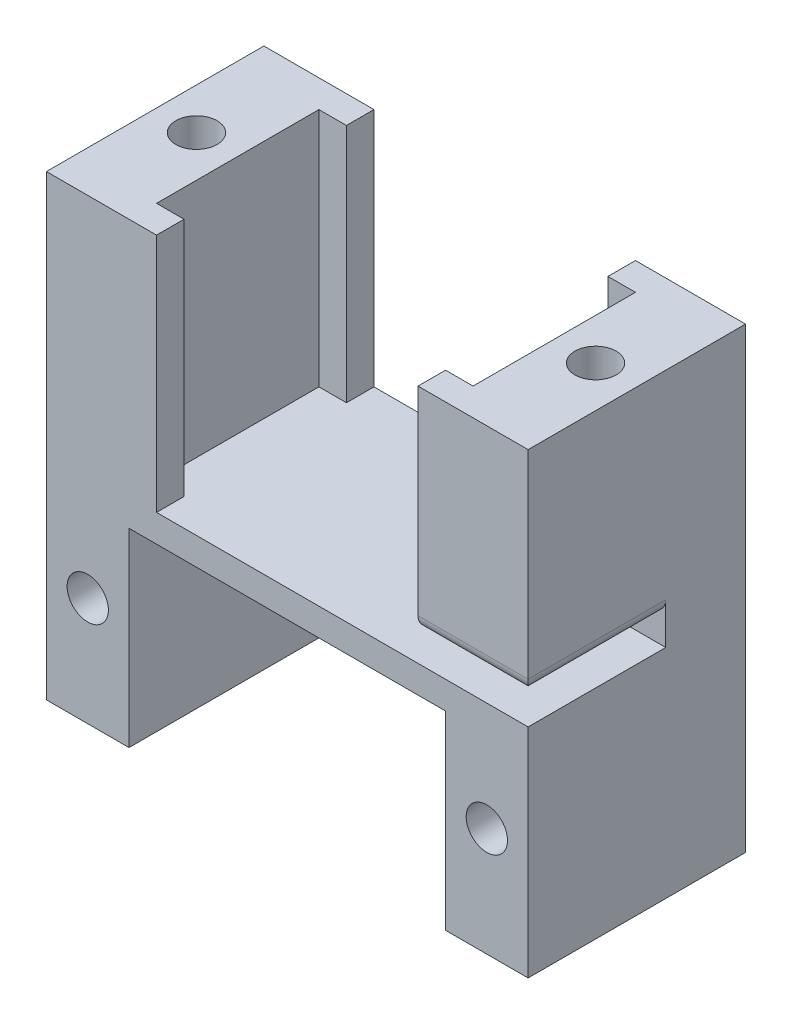
SolidWorks part; units mm, degrees
ref_plane "Front Plane" through (0, 0, 0) normal (0, 0, 1) x (1, 0, 0)
ref_plane "Top Plane" through (0, 0, 0) normal (0, 1, 0) x (1, 0, 0)
ref_plane "Right Plane" through (0, 0, 0) normal (1, 0, 0) x (0, 0, -1)
sketch "Sketch1" plane through (0, 0, 0) normal (0, 1, 0) x (1, 0, 0)
  line L0 (-3, -5.9) -> (-5, -5.9)
  line L1 (-3, 5.9) -> (3, 5.9) construction
  line L2 (-3, 5.9) -> (-3, -5.9)
  line L3 (-3, -5.9) -> (3, -5.9) construction
  line L4 (3, 5.9) -> (3, -5.9)
  line L5 (-3, 5.9) -> (3, -5.9) construction
  line L6 (-3, -5.9) -> (3, 5.9) construction
  line L7 (0, 0) -> (-3, 0) construction
  line L8 (-5, -5.9) -> (-5, -7.9)
  line L9 (-5, -7.9) -> (3, -7.9)
  line L10 (3, -7.9) -> (3, -5.9)
  line L11 (-3, 5.9) -> (-5, 5.9)
  line L12 (-5, 5.9) -> (-5, 7.9)
  line L13 (3, 7.9) -> (3, 5.9)
  line L14 (-5, 7.9) -> (3, 7.9)
  circle A0 centre (0, 0) radius 1.5
  point P0 (0, 0)
extrude "Boss-Extrude1" add sketch "Sketch1" against normal blind 19.45 contours L14 L12 L11 L2 L0 L8 L9 L10 L4 L13 A0
sketch "Sketch2" plane through (0, -19.45, 0) normal (0, -1, 0) x (1, 0, 0)
  circle A0 centre (0, 0) radius 1.5 construction
  circle A1 centre (0, 0) radius 1.5
extrude "Boss-Extrude2" add sketch "Sketch2" against normal blind 5
sketch "Sketch3" plane through (0, 0, 0) normal (0, 1, 0) x (1, 0, 0)
  line L0 (-3, -5.9) -> (-26, -5.9) construction
  line L1 (-14.5, -5.9) -> (-14.5, 3.6808) construction
sketch3d "3DSketch1"
  line L0 (-14.5, 0, 5.9) -> (-14.5, 0, -3.6808) construction
ref_plane "Plane1" through (-14.5, 0, 0) normal (-1, 0, 0) x (0, 0, 1)
mirror "Mirror2" about plane through (-14.5, 0, 0) normal (-1, 0, 0) of bodies 102
sketch "Sketch5" plane through (0, -19.45, 0) normal (0, -1, 0) x (1, 0, 0)
  line L0 (-32, 7.9) -> (3, 7.9)
  line L1 (3, 7.9) -> (3, -7.9)
  line L2 (3, -7.9) -> (-32, -7.9)
  line L3 (-32, -7.9) -> (-32, 7.9)
extrude "Boss-Extrude3" add sketch "Sketch5" against normal blind 2
sketch "Sketch6" plane through (0, 0, 7.9) normal (0, 0, 1) x (1, 0, 0)
  line L0 (-3, -31.25) -> (-5, -31.25)
  line L1 (-3, -19.45) -> (3, -19.45) construction
  line L2 (-3, -19.45) -> (-3, -31.25)
  line L3 (-3, -31.25) -> (3, -31.25) construction
  line L4 (3, -19.45) -> (3, -31.25)
  line L5 (-3, -19.45) -> (3, -31.25) construction
  line L6 (-3, -31.25) -> (3, -19.45) construction
  line L7 (0, -25.35) -> (-3, -25.35) construction
  line L8 (-5, -31.25) -> (-5, -33.25)
  line L9 (-5, -33.25) -> (3, -33.25)
  line L10 (3, -33.25) -> (3, -31.25)
  line L11 (-3, -19.45) -> (-5, -19.45)
  line L12 (-5, -19.45) -> (-5, -17.45)
  line L13 (3, -17.45) -> (3, -19.45)
  line L14 (-5, -17.45) -> (3, -17.45)
  line L15 (-32, -19.45) -> (3, -19.45) construction
  line L16 (-32, -19.45) -> (3, -19.45)
  line L17 (-14.5, -19.45) -> (-14.5, -10.6217) construction
  line L18 (-29, -25.35) -> (-26, -25.35) construction
  line L19 (-26, -31.25) -> (-32, -19.45) construction
  line L20 (-26, -19.45) -> (-32, -31.25) construction
  line L21 (-26, -31.25) -> (-32, -31.25) construction
  line L22 (-26, -19.45) -> (-32, -19.45) construction
  line L23 (-24, -17.45) -> (-32, -17.45)
  line L24 (-32, -17.45) -> (-32, -19.45)
  line L25 (-24, -19.45) -> (-24, -17.45)
  line L26 (-26, -19.45) -> (-24, -19.45)
  line L27 (-32, -33.25) -> (-32, -31.25)
  line L28 (-24, -33.25) -> (-32, -33.25)
  line L29 (-24, -31.25) -> (-24, -33.25)
  line L30 (-32, -19.45) -> (-32, -31.25)
  line L31 (-26, -19.45) -> (-26, -31.25)
  line L32 (-26, -31.25) -> (-24, -31.25)
  circle A0 centre (0, -25.35) radius 1.5
  circle A1 centre (-29, -25.35) radius 1.5
  point P0 (0, -25.35)
  point P31 (-29, -25.35)
  line M27 (-32, -19.45) -> (3, -19.45)
extrude "Boss-Extrude4" add sketch "Sketch6" against normal up to surface (15.8 mm away) contours L32 L31 L30 L27 L28 L29 A1 M27 | L9 L10 L4 L2 L0 L8 A0 M27 up to face at (-14.5, -9.225, -7.9)
sketch "Sketch7" plane through (0, 0, 7.9) normal (0, 0, 1) x (1, 0, 0)
  line L1 (-5, -31.25) -> (-24, -31.25)
  line L2 (-5, -31.25) -> (-5, -33.25)
  line L3 (-5, -33.25) -> (-24, -33.25)
  line L4 (-24, -31.25) -> (-24, -33.25)
extrude "Boss-Extrude5" add sketch "Sketch7" against normal up to surface (15.8 mm away) up to face at (-14.5, -20.7375, -7.9)
sketch "Sketch8" plane through (0, 0, 7.9) normal (0, 0, 1) x (1, 0, 0)
  line L0 (-5, -17.45) -> (3, -17.45)
  line L1 (3, -33.25) -> (3, 0) construction
  line L2 (3, -17.45) -> (3, -15.45)
  line L3 (3, -15.45) -> (-5, -15.45)
  line L4 (-5, -17.45) -> (-5, 0) construction
  line L5 (-5, -15.45) -> (-5, -17.45)
extrude "Cut-Extrude1" cut sketch "Sketch8" against normal blind 10
fillet "Fillet1" radius 1 2 edges at (-1, -15.45, 7.9) (3, -15.45, 2.9)
sketch "Sketch9" plane through (0, 0, 7.9) normal (0, 0, 1) x (1, 0, 0)
  line L0 (-26, -31.25) -> (-26, -33.25)
  line L1 (3, -33.25) -> (-32, -33.25) construction
  line L2 (-26, -33.25) -> (-3, -33.25)
  line L3 (-3, -33.25) -> (-3, -31.25)
  line L4 (-3, -31.25) -> (-26, -31.25)
extrude "Cut-Extrude2" cut sketch "Sketch9" against normal blind 44
fillet "Fillet2" radius 1 2 edges at (-3, -26.35, -7.9) (-26, -26.35, -7.9)
